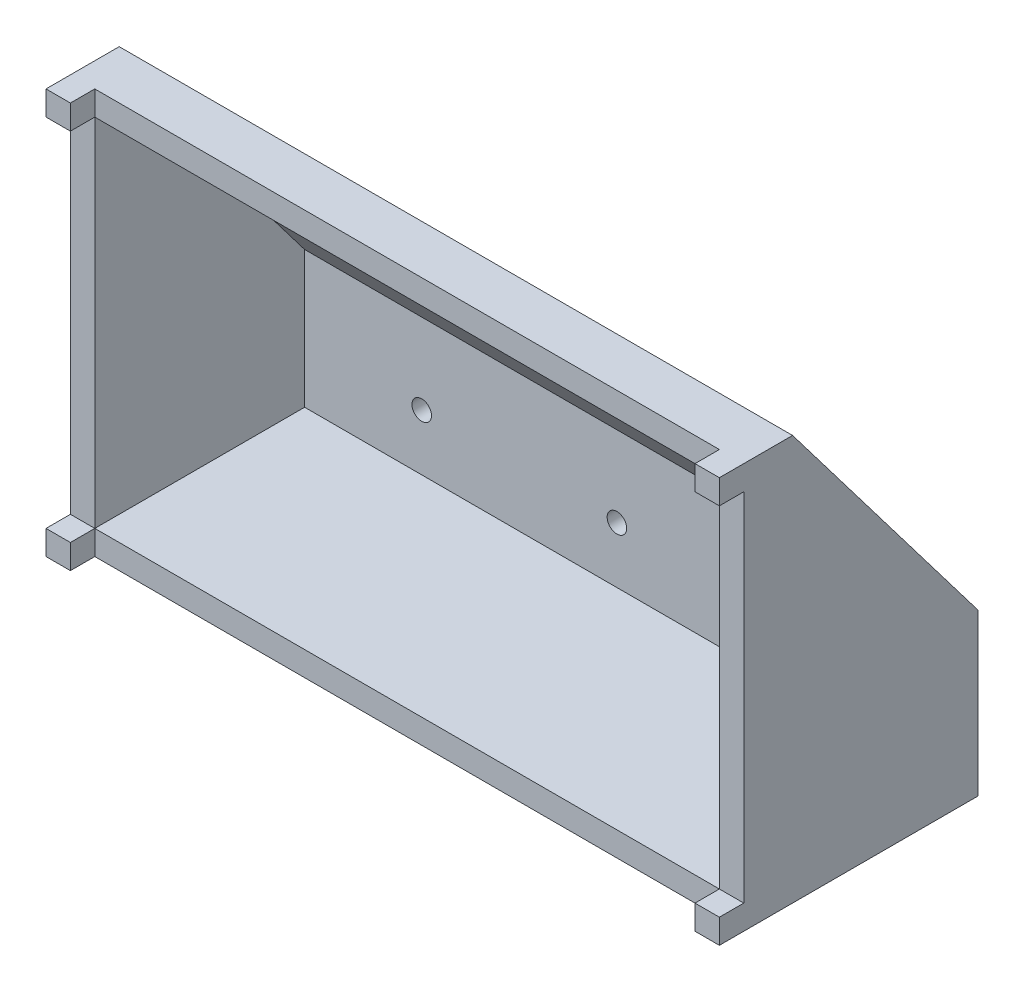
SolidWorks part; units mm, degrees
ref_plane "Ebene vorne" through (0, 0, 0) normal (0, 0, 1) x (1, 0, 0)
ref_plane "Ebene oben" through (0, 0, 0) normal (0, 1, 0) x (1, 0, 0)
ref_plane "Ebene rechts" through (0, 0, 0) normal (1, 0, 0) x (0, 0, -1)
sketch "Sketch1" plane through (0, 0, 0) normal (0, 0, 1) x (1, 0, 0)
  line L1 (-69, -41.5) -> (69, -41.5)
  line L2 (-69, -41.5) -> (-69, 41.5)
  line L3 (-69, 41.5) -> (69, 41.5)
  line L4 (69, -41.5) -> (69, 41.5)
  line L5 (-69, -41.5) -> (69, 41.5) construction
  line L6 (-69, 41.5) -> (69, -41.5) construction
  line L7 (-64, -36.5) -> (64, -36.5)
  line L8 (-64, -36.5) -> (-64, 36.5)
  line L9 (-64, 36.5) -> (64, 36.5)
  line L10 (64, -36.5) -> (64, 36.5)
  line L11 (-64, -36.5) -> (64, 36.5) construction
  line L12 (-64, 36.5) -> (64, -36.5) construction
  point P0 (0, 0)
  point P5 (0, 0)
  dimension "D1" = 138
  dimension "D2" = 83
  dimension "D3" = 128
  dimension "D4" = 73
extrude "Boss-Extrude1" add sketch "Sketch1" along normal blind 10
sketch "Sketch2" plane through (0, 0, 10) normal (0, 0, 1) x (1, 0, 0)
  line L1 (64, 36.5) -> (69, 36.5)
  line L2 (64, 36.5) -> (64, 41.5)
  line L3 (64, 41.5) -> (69, 41.5)
  line L4 (69, 36.5) -> (69, 41.5)
  line L5 (64, -36.5) -> (69, -36.5)
  line L6 (64, -36.5) -> (64, -41.5)
  line L7 (64, -41.5) -> (69, -41.5)
  line L8 (69, -36.5) -> (69, -41.5)
  line L9 (-64, -36.5) -> (-69, -36.5)
  line L10 (-64, -36.5) -> (-64, -41.5)
  line L11 (-64, -41.5) -> (-69, -41.5)
  line L12 (-69, -36.5) -> (-69, -41.5)
  line L13 (-64, 36.5) -> (-69, 36.5)
  line L14 (-64, 36.5) -> (-64, 41.5)
  line L15 (-64, 41.5) -> (-69, 41.5)
  line L16 (-69, 36.5) -> (-69, 41.5)
extrude "Boss-Extrude2" add sketch "Sketch2" along normal blind 5
sketch "Sketch3" plane through (0, 0, 0) normal (0, 0, -1) x (-1, 0, 0)
  line L0 (69, -41.5) -> (-69, -41.5)
  line L1 (69, -41.5) -> (69, -36.5)
  line L2 (-69, -41.5) -> (-69, -36.5)
  line L3 (69, -36.5) -> (-69, -36.5)
  line L4 (64, -36.5) -> (-64, -36.5) construction
  dimension "D1" = 0
extrude "Boss-Extrude3" add sketch "Sketch3" along normal blind 38
ref_plane "Plane1" through (0, 0, -38) normal (0, 0, 1) x (1, 0, 0)
sketch "Sketch6" plane through (0, 0, -38) normal (0, 0, 1) x (1, 0, 0)
  line L1 (69, -36.5) -> (-69, -36.5)
  line L2 (69, -36.5) -> (69, -8.5)
  line L3 (69, -8.5) -> (-69, -8.5)
  line L4 (-69, -36.5) -> (-69, -8.5)
  dimension "D1" = 28
extrude "Boss-Extrude4" add sketch "Sketch6" along normal blind 5
ref_plane "Plane2" through (0, 15.1942, -19.9924) normal (0, -0.6051, 0.7962) x (1, 0, 0)
sketch "Sketch8" plane through (69, 0, 0) normal (1, 0, 0) x (0, 0, -1)
  line L0 (0, 41.5) -> (38, -8.5)
  line L1 (0, 41.5) -> (-5, 41.5)
  line L2 (38, -8.5) -> (33, -8.5)
  line L3 (-5, 41.5) -> (33, -8.5)
extrude "Boss-Extrude5" add sketch "Sketch8" against normal through all
sketch "Sketch9" plane through (69, 0, 0) normal (1, 0, 0) x (0, 0, -1)
  line L0 (0, 34.9211) -> (33, -8.5)
  line L1 (33, -8.5) -> (33, -36.5)
  line L2 (33, -36.5) -> (0, -36.5)
  line L3 (0, -36.5) -> (0, 34.9211)
extrude "Boss-Extrude6" add sketch "Sketch9" against normal blind 5
sketch "Sketch10" plane through (-69, 0, 0) normal (-1, 0, 0) x (0, 0, 1)
  line L0 (0, 34.9211) -> (0, -36.5)
  line L1 (0, -36.5) -> (-33, -36.5)
  line L2 (-33, -36.5) -> (-33, -8.5)
  line L3 (-33, -8.5) -> (0, 34.9211)
extrude "Boss-Extrude7" add sketch "Sketch10" against normal blind 5
ref_plane "Plane3" through (69, 41.5, 0) normal (0, 0.7962, 0.6051) x (1, 0, 0)
sketch "Sketch14" plane through (0, 15.1942, -19.9924) normal (0, 0.6051, -0.7962) x (-1, 0, 0)
  line L0 (69, 1.6401) -> (-69, 1.6401) construction
  line L1 (69, -29.7605) -> (69, 33.0407) construction
  line L2 (-69, -29.7605) -> (-69, 33.0407) construction
  line L4 (-1.4947, 11.6401) -> (-52.4947, 11.6401)
  line L5 (-1.4947, 11.6401) -> (-1.4947, -8.3599)
  line L6 (-1.4947, -8.3599) -> (-52.4947, -8.3599)
  line L7 (-52.4947, 11.6401) -> (-52.4947, -8.3599)
  line L8 (-1.4947, 11.6401) -> (-52.4947, -8.3599) construction
  line L9 (-1.4947, -8.3599) -> (-52.4947, 11.6401) construction
  point P6 (-26.9947, 1.6401)
  dimension "D1" = 51
  dimension "D2" = 20
extrude "Cut-Extrude1" cut sketch "Sketch14" against normal up to next
sketch "Sketch16" plane through (0, 15.1942, -19.9924) normal (0, 0.6051, -0.7962) x (-1, 0, 0)
  line L0 (69, 1.6401) -> (-70.2572, 1.6401) construction
  line L1 (69, -29.7605) -> (69, 33.0407) construction
  line L3 (54, 8.1401) -> (39, 8.1401)
  line L4 (54, 8.1401) -> (54, -4.8599)
  line L5 (54, -4.8599) -> (39, -4.8599)
  line L6 (39, 8.1401) -> (39, -4.8599)
  line L7 (54, 8.1401) -> (39, -4.8599) construction
  line L8 (54, -4.8599) -> (39, 8.1401) construction
  point P4 (46.5, 1.6401)
  dimension "D1" = 13
  dimension "D2" = 15
  dimension "D3" = 15
extrude "Cut-Extrude2" cut sketch "Sketch16" against normal blind 2
sketch "Sketch17" plane through (0, 13.9841, -18.4001) normal (0, 0.6051, -0.7962) x (-1, 0, 0)
  line L0 (54, 8.1401) -> (39, 8.1401) construction
  line L1 (39, -4.8599) -> (42, -4.8599)
  line L2 (39, -4.8599) -> (39, 8.1401)
  line L3 (39, 8.1401) -> (42, 8.1401)
  line L4 (42, -4.8599) -> (42, 8.1401)
  line L6 (54, -4.8599) -> (51, -4.8599)
  line L7 (54, -4.8599) -> (54, 8.1401)
  line L8 (54, 8.1401) -> (51, 8.1401)
  line L9 (51, -4.8599) -> (51, 8.1401)
  dimension "D1" = 3
  dimension "D2" = 3
extrude "Cut-Extrude3" cut sketch "Sketch17" against normal up to next
sketch "Sketch18" plane through (0, 12.7855, -16.823) normal (0, -0.6051, 0.7962) x (1, 0, 0)
  line L0 (1.4947, 11.6401) -> (52.4947, 11.6401) construction
  line L1 (52.4947, 11.6401) -> (52.4947, -8.3599) construction
  line L2 (1.4947, -8.3599) -> (1.4947, 11.6401) construction
  line L4 (52.4947, -8.3599) -> (1.4947, -8.3599) construction
  circle A0 centre (49.1947, -10.1399) radius 1
  circle A1 centre (4.7947, -10.1399) radius 1
  circle A2 centre (4.7947, 13.4201) radius 1
  circle A3 centre (49.1947, 13.4201) radius 1
  dimension "D1" = 2
  dimension "D2" = 2
  dimension "D3" = 2
  dimension "D4" = 2
  dimension "D5" = 1.78
  dimension "D6" = 3.3
  dimension "D7" = 3.3
  dimension "D8" = 3.3
  dimension "D9" = 3.3
  dimension "D10" = 1.78
  dimension "D11" = 0
  dimension "D12" = 0
extrude "Cut-Extrude4" cut sketch "Sketch18" against normal blind 3.5
sketch "Sketch19" plane through (0, 0, -38) normal (0, 0, -1) x (-1, 0, 0)
  line L0 (69, -25) -> (-69, -25) construction
  line L1 (69, -41.5) -> (69, -8.5) construction
  line L2 (-69, -8.5) -> (-69, -41.5) construction
  circle A0 centre (40, -25) radius 2
  circle A1 centre (0, -25) radius 2
  circle A2 centre (-40, -25) radius 2
  dimension "D1" = 4
  dimension "D2" = 4
  dimension "D3" = 4
  dimension "D4" = 40
  dimension "D5" = 40
  dimension "D7" = 29
extrude "Cut-Extrude5" cut sketch "Sketch19" against normal up to next
sketch "Sketch20" plane through (0, 12.7855, -16.823) normal (0, -0.6051, 0.7962) x (1, 0, 0)
  line L0 (26.9947, -8.3599) -> (26.9947, 11.6401) construction
  line L1 (52.4947, -8.3599) -> (1.4947, -8.3599) construction
  line L2 (1.4947, 11.6401) -> (52.4947, 11.6401) construction
  line L3 (34.4947, -12.3599) -> (34.4947, -8.3599)
  line L4 (34.4947, -12.3599) -> (19.4947, -12.3599)
  line L5 (34.4947, -8.3599) -> (19.4947, -8.3599)
  line L6 (19.4947, -12.3599) -> (19.4947, -8.3599)
  line L7 (34.4947, -12.3599) -> (19.4947, -8.3599) construction
  line L8 (34.4947, -8.3599) -> (19.4947, -12.3599) construction
  point P7 (26.9947, -10.3599)
  dimension "D1" = 0
  dimension "D2" = 4
  dimension "D3" = 15
  dimension "D4" = 0
extrude "Cut-Extrude6" cut sketch "Sketch20" against normal blind 3
